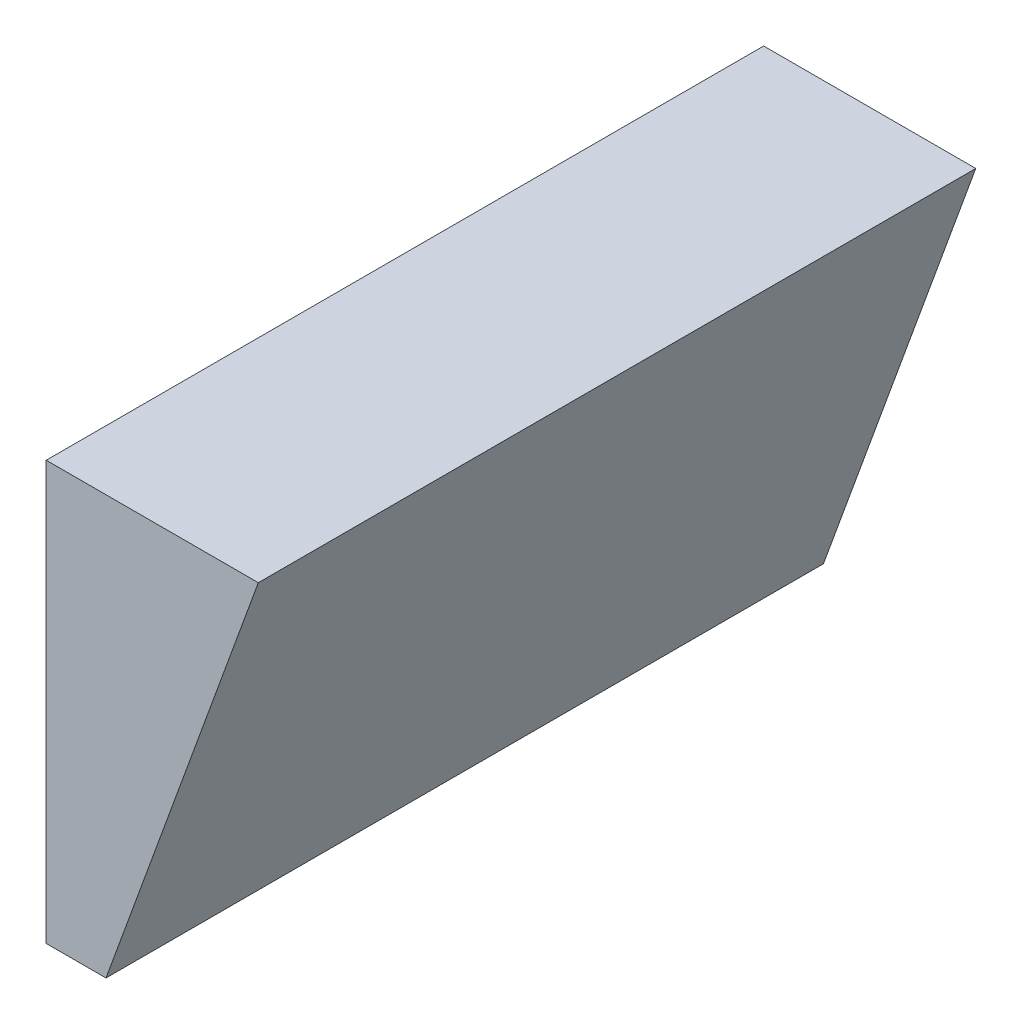
SolidWorks part; units mm, degrees
ref_plane "Front Plane" through (0, 0, 0) normal (0, 0, 1) x (1, 0, 0)
ref_plane "Top Plane" through (0, 0, 0) normal (0, 1, 0) x (1, 0, 0)
ref_plane "Right Plane" through (0, 0, 0) normal (1, 0, 0) x (0, 0, -1)
sketch "Sketch1" plane through (0, 0, 0) normal (0, 0, 1) x (1, 0, 0)
  line L0 (0, 0) -> (0, 35)
  line L1 (0, 0) -> (5, 0)
  line L2 (5, 0) -> (17.739, 35)
  line L3 (17.739, 35) -> (0, 35)
  dimension "D1" = 20
  dimension "D2" = 35
  dimension "D3" = 5
extrude "Boss-Extrude1" add sketch "Sketch1" along normal blind 60
